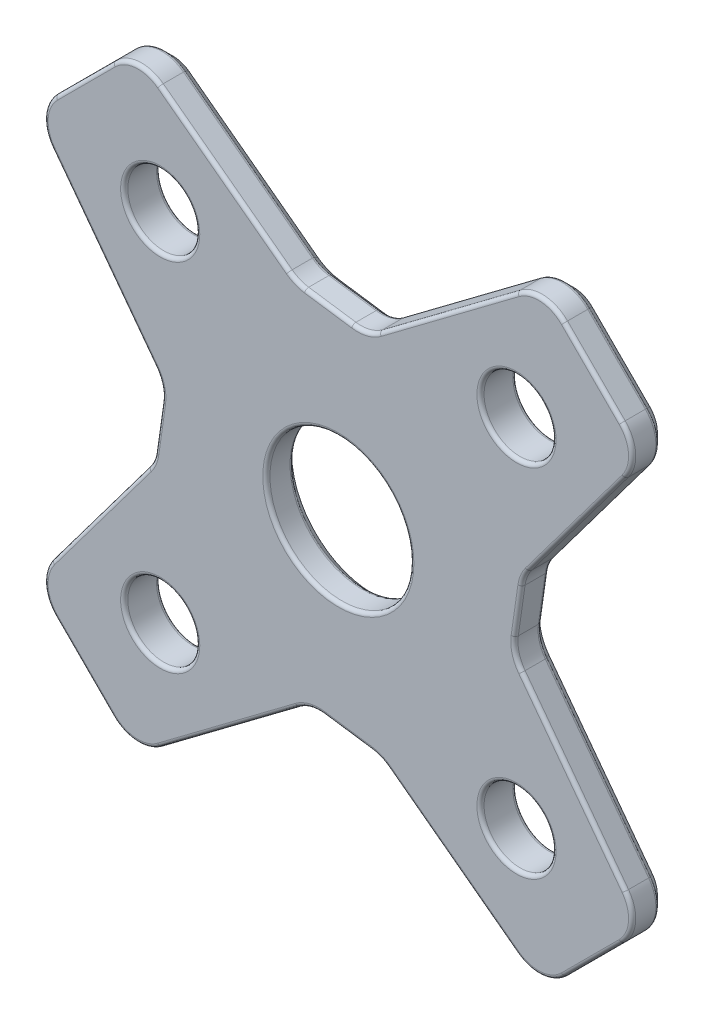
SolidWorks part; units mm, degrees
material "moto_grey"
ref_plane "Front Plane" through (0, 0, 0) normal (0, 0, 1) x (1, 0, 0)
ref_plane "Top Plane" through (0, 0, 0) normal (0, 1, 0) x (1, 0, 0)
ref_plane "Right Plane" through (0, 0, 0) normal (1, 0, 0) x (0, 0, -1)
sketch "Sketch1" plane through (0, 0, 0) normal (0, 0, 1) x (1, 0, 0)
  line L5 (-84.8528, -56.5685) -> (-56.5685, -84.8528)
  line L6 (-84.8528, 56.5685) -> (-56.5685, 84.8528)
  line L11 (56.5685, 84.8528) -> (84.8528, 56.5685)
  line L12 (84.8528, -56.5685) -> (56.5685, -84.8528)
  line L16 (-84.8528, 56.5685) -> (-42.4264, 0)
  line L17 (-42.4264, 0) -> (-84.8528, -56.5685)
  line L18 (-56.5685, -84.8528) -> (0, -42.4264)
  line L19 (0, -42.4264) -> (56.5685, -84.8528)
  line L20 (84.8528, -56.5685) -> (42.4264, 0)
  line L21 (42.4264, 0) -> (84.8528, 56.5685)
  line L22 (56.5685, 84.8528) -> (0, 42.4264)
  line L23 (0, 42.4264) -> (-56.5685, 84.8528)
  line L24 (-70.7107, -70.7107) -> (70.7107, 70.7107)
  line L25 (-70.7107, 70.7107) -> (70.7107, -70.7107)
  circle A0 centre (0, 0) radius 20
  circle A1 centre (-49.4975, -49.4975) radius 10
  circle A2 centre (49.4975, 49.4975) radius 10
  circle A3 centre (49.4975, -49.4975) radius 10
  circle A4 centre (-49.4975, 49.4975) radius 10
  dimension "D1" = 40
  dimension "D2" = 20
  dimension "D4" = 20
  dimension "D3" = 30
  dimension "D5" = 30
  dimension "D6" = 70
extrude "Boss-Extrude1" add sketch "Sketch1" along normal blind 10 contours L25 A4 A0 L24 A2 L11 L22 L23 L6 | L25 A4 L6 L16 L17 L5 L24 A1 A0 | A3 L25 A0 L24 A1 L5 L18 L19 L12 | A3 L25 L12 L20 L21 L11 L24 A2 A0
chamfer "Chamfer1" distance 10 angle 45 4 edges at (0, -42.4264, 5) (42.4264, 0, 5) (0, 42.4264, 5) (-42.4264, 0, 5)
fillet "Fillet1" radius 10 8 edges at (-8, -48.4264, 5) (11.7647, -51.2499, 5) (48.4264, -8, 5) (51.2499, 11.7647, 5) (8, 48.4264, 5) (-11.7647, 51.2499, 5) (-51.2499, -11.7647, 5) (-48.4264, 8, 5)
fillet "Fillet3" radius 10 8 edges at (-84.8528, -56.5685, 5) (-56.5685, -84.8528, 5) (56.5685, -84.8528, 5) (84.8528, -56.5685, 5) (84.8528, 56.5685, 5) (56.5685, 84.8528, 5) (-84.8528, 56.5685, 5) (-56.5685, 84.8528, 5)
chamfer "Chamfer5" distance 3 angle 45 32 edges at (-65.2804, 30.4719, 0) (-49.2246, 7.7955, 0) (-81.6239, 56.3391, 0) (-49.9499, -2.6645, 0) (-70.7107, 70.7107, 0) (-51.5483, -11.6411, 0) (-56.3391, 81.6239, 0) (-66.2181, -31.7222, 0) (-31.7222, 66.2181, 0) (-81.6239, -56.3391, 0) (-11.6411, 51.5483, 0) (-70.7107, -70.7107, 0) (-2.6645, 49.9499, 0) (-56.3391, -81.6239, 0) (7.7955, 49.2246, 0) (-30.4719, -65.2804, 0) (30.4719, 65.2804, 0) (-7.7955, -49.2246, 0) (56.3391, 81.6239, 0) (2.6645, -49.9499, 0) (70.7107, 70.7107, 0) (11.6411, -51.5483, 0) (81.6239, 56.3391, 0) (31.7222, -66.2181, 0) (66.2181, 31.7222, 0) (56.3391, -81.6239, 0) (51.5483, 11.6411, 0) (70.7107, -70.7107, 0) (49.9499, 2.6645, 0) (81.6239, -56.3391, 0) (49.2246, -7.7955, 0) (65.2804, -30.4719, 0)
fillet "Fillet4" radius 1 32 edges at (46.9801, 3.0888, 0) (48.7767, 12.7892, 0) (63.8181, 33.5222, 0) (78.6314, 56.1264, 0) (68.5894, 68.5894, 0) (56.1264, 78.6314, 0) (32.2719, 62.8804, 0) (8.5401, 46.3184, 0) (-3.0888, 46.9801, 0) (-12.7892, 48.7767, 0) (-33.5222, 63.8181, 0) (-56.1264, 78.6314, 0) (-68.5894, 68.5894, 0) (-78.6314, 56.1264, 0) (-62.8804, 32.2719, 0) (-46.3184, 8.5401, 0) (-46.9801, -3.0888, 0) (-48.7767, -12.7892, 0) (-63.8181, -33.5222, 0) (-78.6314, -56.1264, 0) (-68.5894, -68.5894, 0) (-56.1264, -78.6314, 0) (-32.2719, -62.8804, 0) (-8.5401, -46.3184, 0) (3.0888, -46.9801, 0) (12.7892, -48.7767, 0) (33.5222, -63.8181, 0) (56.1264, -78.6314, 0) (68.5894, -68.5894, 0) (78.6314, -56.1264, 0) (62.8804, -32.2719, 0) (46.3184, -8.5401, 0)
fillet "Fillet5" radius 1 32 edges at (81.6239, -56.3391, 3) (70.7107, -70.7107, 3) (56.3391, -81.6239, 3) (31.7222, -66.2181, 3) (11.6411, -51.5483, 3) (2.6645, -49.9499, 3) (-7.7955, -49.2246, 3) (-30.4719, -65.2804, 3) (-56.3391, -81.6239, 3) (-70.7107, -70.7107, 3) (-81.6239, -56.3391, 3) (-66.2181, -31.7222, 3) (-51.5483, -11.6411, 3) (-49.9499, -2.6645, 3) (-49.2246, 7.7955, 3) (-65.2804, 30.4719, 3) (-81.6239, 56.3391, 3) (-70.7107, 70.7107, 3) (-56.3391, 81.6239, 3) (-31.7222, 66.2181, 3) (-11.6411, 51.5483, 3) (-2.6645, 49.9499, 3) (7.7955, 49.2246, 3) (30.4719, 65.2804, 3) (56.3391, 81.6239, 3) (70.7107, 70.7107, 3) (81.6239, 56.3391, 3) (66.2181, 31.7222, 3) (51.5483, 11.6411, 3) (49.9499, 2.6645, 3) (49.2246, -7.7955, 3) (65.2804, -30.4719, 3)
fillet "Fillet6" radius 1 9 edges at (59.4975, -49.4975, 10) (59.4975, -49.4975, 0) (-39.4975, 49.4975, 10) (-39.4975, 49.4975, 0) (-39.4975, -49.4975, 10) (-39.4975, -49.4975, 0) (20, 0, 10) (59.4975, 49.4975, 10) (59.4975, 49.4975, 0)
chamfer "Chamfer6" distance 3 angle 45 1 edges at (20, 0, 0)
fillet "Fillet8" radius 1 1 edges at (20, 0, 3)
fillet "Fillet9" radius 1 1 edges at (23, 0, 0)
fillet "Fillet10" radius 1 32 edges at (70.7107, 70.7107, 10) (81.6239, 56.3391, 10) (66.2181, 31.7222, 10) (51.5483, 11.6411, 10) (49.9499, 2.6645, 10) (49.2246, -7.7955, 10) (65.2804, -30.4719, 10) (81.6239, -56.3391, 10) (70.7107, -70.7107, 10) (56.3391, -81.6239, 10) (31.7222, -66.2181, 10) (11.6411, -51.5483, 10) (2.6645, -49.9499, 10) (-7.7955, -49.2246, 10) (-30.4719, -65.2804, 10) (-56.3391, -81.6239, 10) (-70.7107, -70.7107, 10) (-81.6239, -56.3391, 10) (-66.2181, -31.7222, 10) (-51.5483, -11.6411, 10) (-49.9499, -2.6645, 10) (-49.2246, 7.7955, 10) (-65.2804, 30.4719, 10) (-81.6239, 56.3391, 10) (-70.7107, 70.7107, 10) (-56.3391, 81.6239, 10) (-31.7222, 66.2181, 10) (-11.6411, 51.5483, 10) (-2.6645, 49.9499, 10) (7.7955, 49.2246, 10) (30.4719, 65.2804, 10) (56.3391, 81.6239, 10)
